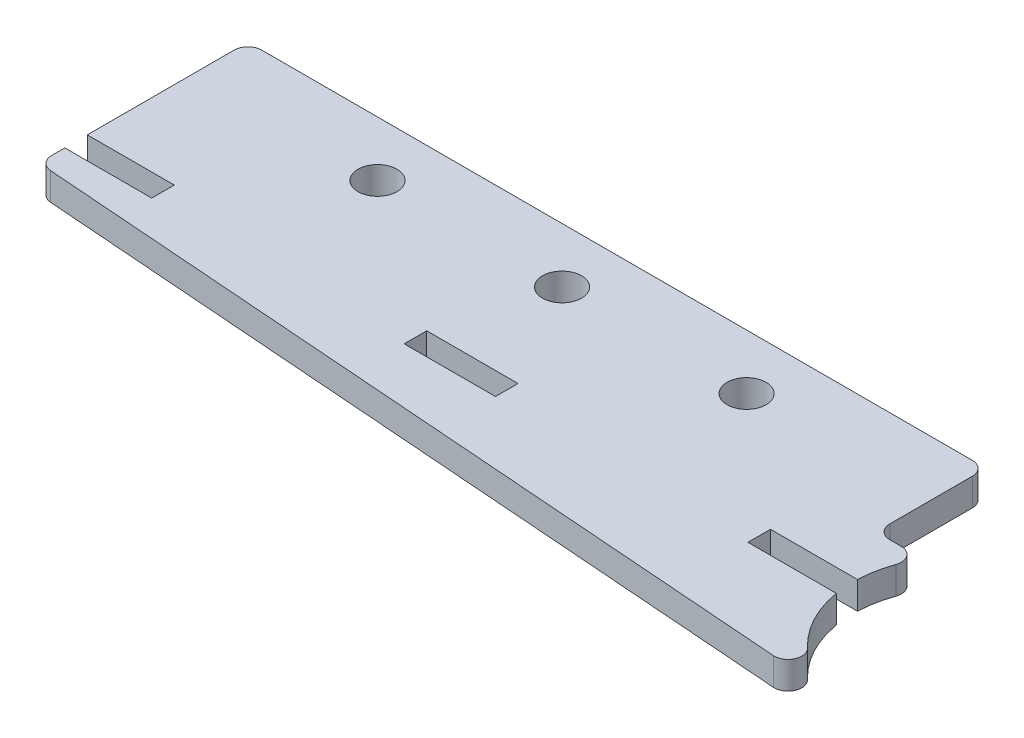
SolidWorks part; units mm, degrees
material "ASTM A36 Steel"
ref_plane "X-Y Datum" through (0, 0, 0) normal (0, 0, 1) x (1, 0, 0)
ref_plane "X-Z Datum" through (0, 0, 0) normal (0, 1, 0) x (1, 0, 0)
ref_plane "Y-Z Datum" through (0, 0, 0) normal (1, 0, 0) x (0, 0, -1)
sketch "Sketch1" plane through (0, 0, 0) normal (0, 1, 0) x (1, 0, 0)
  line L0 (0, 0) -> (-101.6, 0) construction
  line L1 (-101.6, -5.08) -> (0, -12.7)
  line L2 (-101.6, 0) -> (-101.6, 6.35)
  line L3 (-101.6, 6.35) -> (-10.9985, 6.35)
  line L4 (-101.6, 0) -> (-101.6, -5.08)
  circle A0 centre (0, 0) radius 12.7 construction
  arc A1 (0, -12.7) -> (0, 12.7) centre (0, 0) cw
  point P8 (-12.7, 0)
  dimension "D1" = 25.4
  dimension "D2" = 88.9
  dimension "D3" = 6.35
  dimension "D4" = 5.08
extrude "Boss-Extrude1" add sketch "Sketch1" along normal blind 3.175 contours L1 A1 L3 L2 L4
fillet "Fillet1" radius 1.5875 2 edges at (-10.9985, 1.5875, -6.35) (-1.8943, 1.5875, 12.5579)
sketch "Sketch2" plane through (0, 3.175, 0) normal (0, 1, 0) x (1, 0, 0)
  line L0 (-16.384, 2.54) -> (-16.384, 78.612) construction
  line L1 (-101.6, 6.35) -> (-16.384, 6.35)
  line L2 (-101.6, 6.35) -> (-101.6, 19.05)
  line L3 (-101.6, 19.05) -> (-16.384, 19.05)
  line L4 (-16.384, 6.35) -> (-16.384, 19.05)
  dimension "D1" = 12.7
extrude "Boss-Extrude2" add sketch "Sketch2" against normal blind 3.175
fillet "Fillet2" radius 1.5875 4 edges at (-16.384, 1.5875, -6.35) (-16.384, 1.5875, -19.05) (-101.6, 1.5875, -19.05) (-101.6, 1.5875, 5.08)
hole_wizard "M4 Clearance Hole1" positions "Sketch3" profile "Sketch4" hole size "M4" standard "ANSI Metric" end condition through all
sketch "Sketch3" plane through (0, 3.175, 0) normal (0, 1, 0) x (1, 0, 0)
  point P0 (-80.296, 12.7)
  point P3 (-58.992, 12.7)
  point P6 (-37.688, 12.7)
sketch "Sketch4" plane through (-80.296, 3.175, -12.7) normal (1, 0, 0) x (0, 0, 1)
  line L0 (0, 0) -> (0, 3.175)
  line L1 (0, 3.175) -> (2.25, 3.175)
  line L2 (2.25, 3.175) -> (2.25, 0)
  line L5 (2.25, 0) -> (0, 0)
  line L11 (0, -6.35) -> (0, 107.95) construction
  dimension "Thru Hole Dia." = 4.5
  dimension "Thru Hole Depth" = 3.175
sketch "Sketch5" plane through (0, 3.175, 0) normal (0, 1, 0) x (1, 0, 0)
  line L0 (-12.192, -2.0955) -> (-12.192, 0.508)
  line L1 (-12.192, 0.508) -> (-22.733, 0.508)
  line L2 (-22.733, 0.508) -> (-22.733, -2.0955)
  line L3 (-22.733, -2.0955) -> (-12.192, -2.0955)
  line L4 (-51.8795, -2.0955) -> (-51.8795, 0.508)
  line L5 (-51.8795, 0.508) -> (-62.4205, 0.508)
  line L6 (-62.4205, 0.508) -> (-62.4205, -2.0955)
  line L7 (-62.4205, -2.0955) -> (-51.8795, -2.0955)
  line L11 (-12.7, -1.5875) -> (-12.7, 0) construction
  line L12 (-12.7, 0) -> (-22.225, 0) construction
  line L13 (-22.225, 0) -> (-22.225, -1.5875) construction
  line L14 (-22.225, -1.5875) -> (-12.7, -1.5875) construction
  line L15 (-52.3875, -1.5875) -> (-52.3875, 0) construction
  line L16 (-52.3875, 0) -> (-61.9125, 0) construction
  line L17 (-61.9125, 0) -> (-61.9125, -1.5875) construction
  line L18 (-61.9125, -1.5875) -> (-52.3875, -1.5875) construction
  line L19 (-92.075, 0) -> (-101.6, 0)
  line L20 (-92.075, -1.5875) -> (-92.075, 0)
  line L21 (-101.6, -1.5875) -> (-92.075, -1.5875)
  line L22 (-101.6, -3.6071) -> (-101.6, 17.4625) construction
  line L23 (-101.6, -3.6071) -> (-101.6, 17.4625)
  line L24 (-101.6, -2.0955) -> (-91.567, -2.0955)
  line L25 (-91.567, -2.0955) -> (-91.567, 0.508)
  line L26 (-91.567, 0.508) -> (-101.6, 0.508)
  arc A0 (-101.6, -3.6071) -> (-100.1312, -5.1902) centre (-100.0125, -3.6071) ccw construction
  arc A1 (-101.6, -3.6071) -> (-100.1312, -5.1902) centre (-100.0125, -3.6071) ccw
  point P20 (-101.6066, -2.9691)
  point P21 (-92.5907, -4.5449)
  line M8 (-101.6, 17.4625) -> (-101.6, -3.6071)
  arc M12 (-8.7353, -9.2187) -> (-11.9737, 4.2333) centre (0, 0) cw
  dimension "D1" = 0.508
  dimension "D2" = 0.508
extrude "Cut-Extrude1" cut sketch "Sketch5" against normal blind 3.175 contours L21 L20 L19 M8 | L25 L26 L23 L19 L20 L21 L24 M8 | L6 L7 L4 L5 | L2 L3 L1 M12
